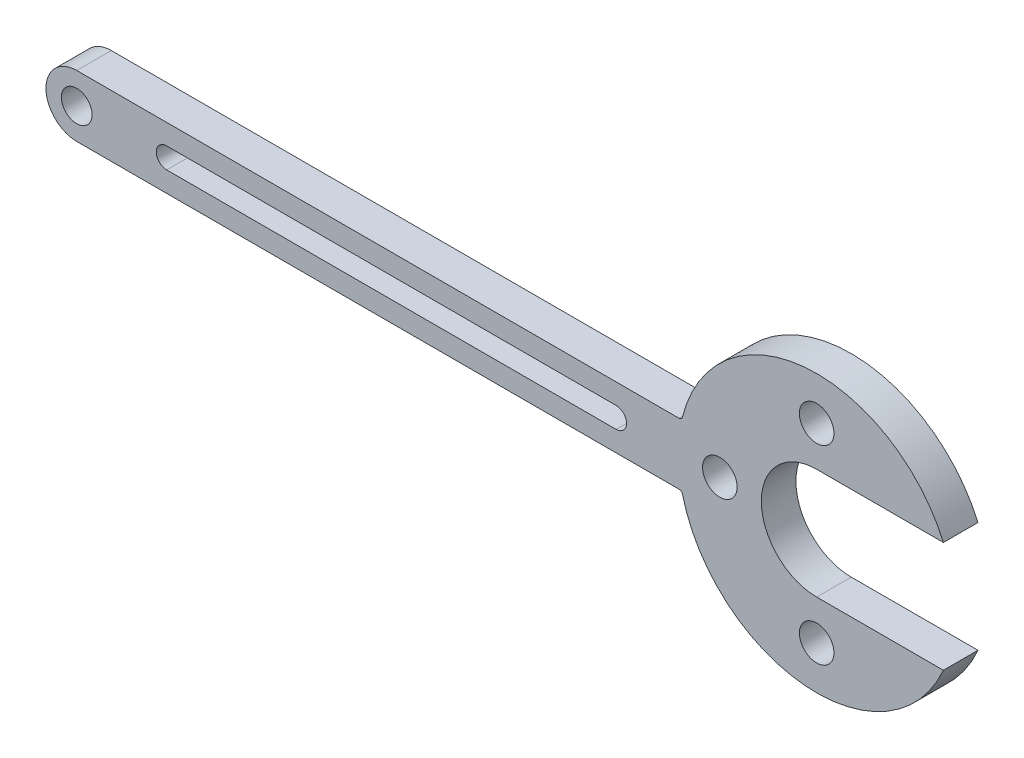
SolidWorks part; units mm, degrees
ref_plane "Front Plane" through (0, 0, 0) normal (0, 0, 1) x (1, 0, 0)
ref_plane "Top Plane" through (0, 0, 0) normal (0, 1, 0) x (1, 0, 0)
ref_plane "Right Plane" through (0, 0, 0) normal (1, 0, 0) x (0, 0, -1)
sketch "Sketch1" plane through (0, 0, 0) normal (0, 0, 1) x (1, 0, 0)
  line L0 (0, 0) -> (0, -50000) construction
  line L1 (0, 0) -> (-50000, 0) construction
  line L2 (36.6606, 16) -> (0, 16)
  line L3 (0, -16) -> (36.6606, -16)
  line L4 (-39.7897, 8.8882) -> (-214, 8.8882)
  line L5 (-214, -8.8882) -> (-39.7897, -8.8882)
  line L6 (-188, 0) -> (-58, 0) construction
  line L7 (-188, 3) -> (-58, 3)
  line L8 (-188, -3) -> (-58, -3)
  arc A0 (36.6606, 16) -> (-38.8193, 9.647) centre (0, 0) ccw
  circle A1 centre (0, 27.5) radius 5
  circle A2 centre (-28, 0) radius 5
  circle A3 centre (0, -27.5) radius 5
  arc A4 (0, 16) -> (0, -16) centre (0, 0) ccw
  arc A5 (-214, 8.8882) -> (-214, -8.8882) centre (-214, 0) ccw
  arc A6 (-38.8193, -9.647) -> (36.6606, -16) centre (0, 0) ccw
  arc A7 (-39.7897, -8.8882) -> (-38.8193, -9.647) centre (-39.7897, -9.8882) cw
  arc A8 (-39.7897, 8.8882) -> (-38.8193, 9.647) centre (-39.7897, 9.8882) ccw
  circle A9 centre (-214, 0) radius 4.435
  arc A10 (-188, 3) -> (-188, -3) centre (-188, 0) ccw
  arc A11 (-58, -3) -> (-58, 3) centre (-58, 0) ccw
  point P25 (-39, -8.8882)
  point P28 (-39, 8.8882)
  point P31 (-123, 0)
  dimension "D1" = 10
  dimension "D2" = 10
  dimension "D3" = 10
  dimension "D5" = 80
  dimension "D6" = 55
  dimension "D7" = 27.5
  dimension "D10" = 16
  dimension "D12" = 175
  dimension "D15" = 1
  dimension "D16" = 130
  dimension "D17" = 3
  dimension "D20" = 8.87
  dimension "D4" = 28
  dimension "D8" = 27.5
  dimension "D9" = 27.5
  dimension "D11" = 32
  dimension "D13" = 175
  dimension "D14" = 8.8882
  dimension "D18" = 26
  dimension "D19" = 30
extrude "Boss-Extrude1" add sketch "Sketch1" along normal mid plane 10
